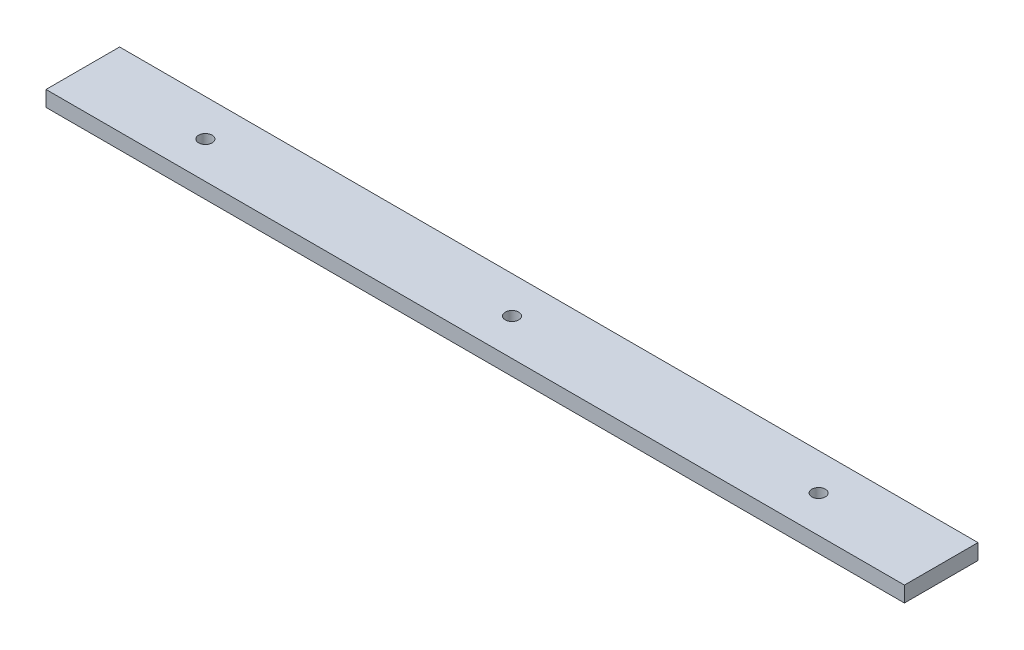
SolidWorks part; units mm, degrees
ref_plane "Front Plane" through (0, 0, 0) normal (0, 0, 1) x (1, 0, 0)
ref_plane "Top Plane" through (0, 0, 0) normal (0, 1, 0) x (1, 0, 0)
ref_plane "Right Plane" through (0, 0, 0) normal (1, 0, 0) x (0, 0, -1)
sketch "Sketch1" plane through (0, 0, 0) normal (0, 1, 0) x (1, 0, 0)
  line L1 (0, 0) -> (350, 0)
  line L2 (0, 0) -> (0, 30)
  line L3 (0, 30) -> (350, 30)
  line L4 (350, 0) -> (350, 30)
  dimension "D1" = 350
  dimension "D2" = 30
extrude "Boss-Extrude1" add sketch "Sketch1" along normal blind 6.35
sketch "Sketch2" plane through (0, 6.35, 0) normal (0, 1, 0) x (1, 0, 0)
  line L0 (0, 15) -> (350, 15) construction
  line L1 (0, 30) -> (0, 0) construction
  line L2 (350, 0) -> (350, 30) construction
  point P6 (50, 15)
  point P7 (300, 15)
  point P8 (175, 15)
  dimension "D1" = 50
  dimension "D2" = 50
hole_wizard "M5 Clearance Hole1" positions "Sketch3" profile "Sketch4" hole size "M5" standard "ANSI Metric" end condition through all
sketch "Sketch3" plane through (0, 6.35, 0) normal (0, 1, 0) x (1, 0, 0)
  line L0 (0, 15) -> (350, 15) construction
  point P0 (50, 15)
  point P3 (175, 15)
  point P7 (300, 15)
sketch "Sketch4" plane through (50, 6.35, -15) normal (1, 0, 0) x (0, 0, 1)
  line L0 (0, 0) -> (0, 6.35)
  line L1 (0, 6.35) -> (2.75, 6.35)
  line L2 (2.75, 6.35) -> (2.75, 0)
  line L5 (2.75, 0) -> (0, 0)
  line L11 (0, -6.35) -> (0, 107.95) construction
  dimension "Thru Hole Dia." = 5.5
  dimension "Thru Hole Depth" = 6.35
